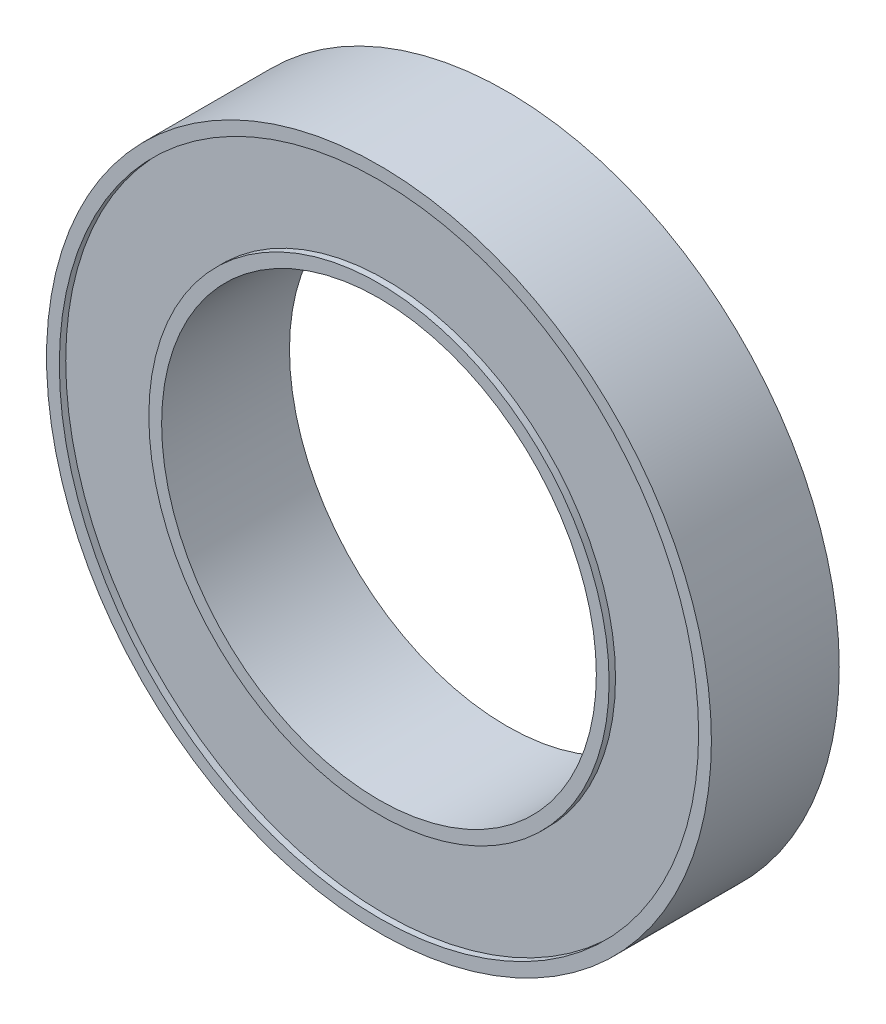
SolidWorks part; units mm, degrees
ref_plane "Front Plane" through (0, 0, 0) normal (0, 0, 1) x (1, 0, 0)
ref_plane "Top Plane" through (0, 0, 0) normal (0, 1, 0) x (1, 0, 0)
ref_plane "Right Plane" through (0, 0, 0) normal (1, 0, 0) x (0, 0, -1)
sketch "Sketch1" plane through (0, 0, 0) normal (0, 0, 1) x (1, 0, 0)
  circle A0 centre (0, 0) radius 8.5
  circle A1 centre (0, 0) radius 13
  dimension "D1" = 26
  dimension "D2" = 17
extrude "Boss-Extrude1" add sketch "Sketch1" along normal mid plane 5
sketch "Sketch2" plane through (0, 0, 2.5) normal (0, 0, 1) x (1, 0, 0)
  circle A2 centre (0, 0) radius 12.5
  circle A3 centre (0, 0) radius 12.5
  circle A5 centre (0, 0) radius 9
  circle A6 centre (0, 0) radius 9
  dimension "D1" = 0.5
  dimension "D2" = 0.5
extrude "Cut-Extrude1" cut sketch "Sketch2" against normal blind 0.25 contours A3 | A6
mirror "Mirror1" about plane through (0, 0, 0) normal (0, 0, 1) of "Cut-Extrude1"
equation "\"Bearing Internal 'd'\"= 17mm"
equation "\"Bearing External 'd'\"= 26mm"
equation "\"Bearing Width\"= 5mm"
equation "\"D1@Sketch1\"=\"Bearing External 'd'\"''''''"
equation "\"D2@Sketch1\"=\"Bearing Internal 'd'\"''''''"
equation "\"D1@Boss-Extrude1\"=\"Bearing Width\""
